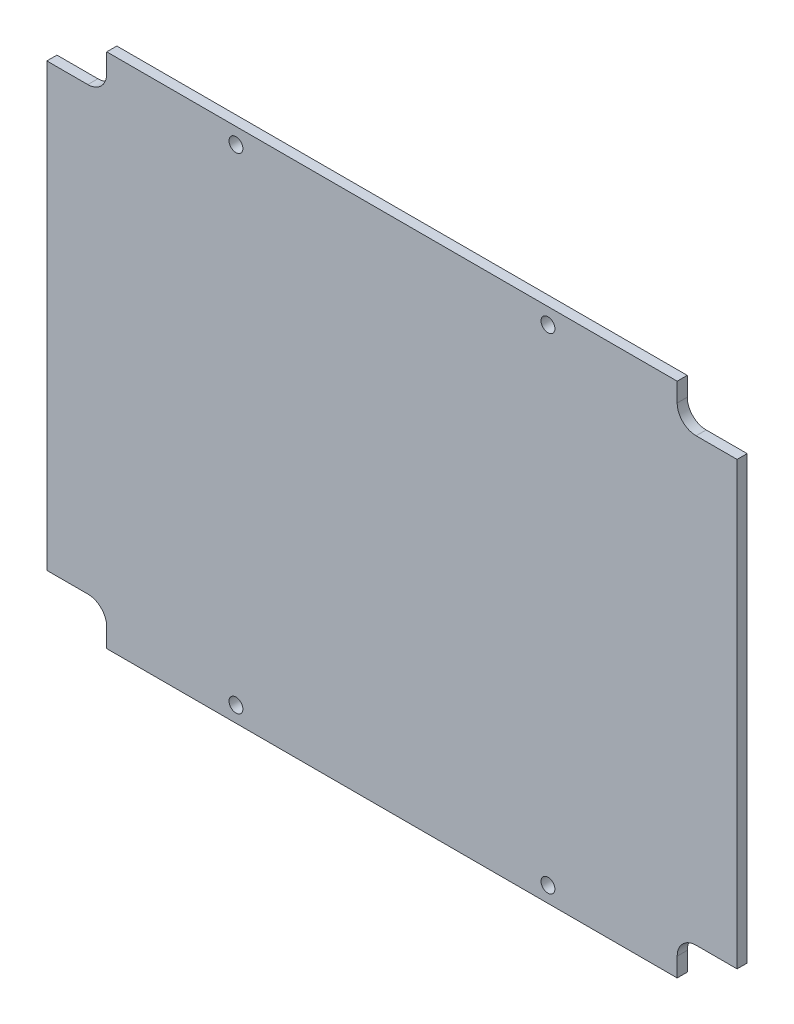
SolidWorks part; units mm, degrees
ref_plane "Front Plane" through (0, 0, 0) normal (0, 0, 1) x (1, 0, 0)
ref_plane "Top Plane" through (0, 0, 0) normal (0, 1, 0) x (1, 0, 0)
ref_plane "Right Plane" through (0, 0, 0) normal (1, 0, 0) x (0, 0, -1)
sketch "Sketch1" plane through (0, 0, 0) normal (0, 0, 1) x (1, 0, 0)
  line L0 (-55.4936, 79.9519) -> (-45.9936, 79.9519)
  line L1 (-45.9936, 85.9519) -> (44.5064, 85.9519)
  line L2 (54.0064, 79.9519) -> (54.0064, 9.9519)
  line L3 (-45.9936, 79.9519) -> (-45.9936, 85.9519)
  line L4 (-55.4936, 79.9519) -> (-55.4936, 9.9519)
  line L5 (-45.9936, 3.9519) -> (44.5064, 3.9519)
  line L6 (-55.4936, 9.9519) -> (-45.9936, 9.9519)
  line L7 (-45.9936, 9.9519) -> (-45.9936, 3.9519)
  line L8 (44.5064, 3.9519) -> (44.5064, 9.9519)
  line L9 (44.5064, 9.9519) -> (54.0064, 9.9519)
  line L10 (44.5064, 85.9519) -> (44.5064, 79.9519)
  line L11 (44.5064, 79.9519) -> (54.0064, 79.9519)
  circle A0 centre (-25.4936, 83.4519) radius 1.1
  circle A1 centre (24.0064, 83.4519) radius 1.1
  circle A2 centre (24.0064, 6.4519) radius 1.1
  circle A3 centre (-25.4936, 6.4519) radius 1.1
  dimension "D1" = 2.2
  dimension "D2" = 2.5
  dimension "D3" = 82
  dimension "D4" = 109.5
  dimension "D5" = 2.5
  dimension "D6" = 9.5
  dimension "D7" = 2.5
  dimension "D8" = 2.5
  dimension "D9" = 30
  dimension "D10" = 30
  dimension "D11" = 30
  dimension "D12" = 30
  dimension "D13" = 6
extrude "Boss-Extrude1" add sketch "Sketch1" along normal blind 1.6
fillet "Fillet1" radius 3 4 edges at (-45.9936, 79.9519, 0.8) (44.5064, 79.9519, 0.8) (44.5064, 9.9519, 0.8) (-45.9936, 9.9519, 0.8)
